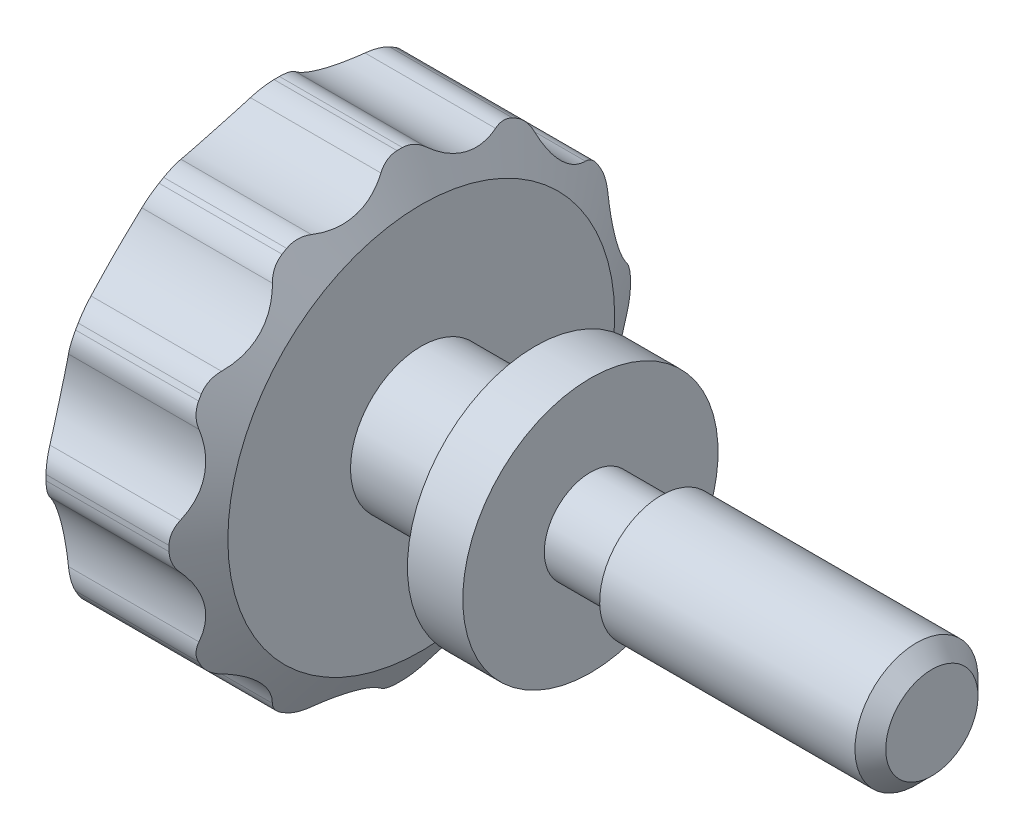
SolidWorks part; units mm, degrees
ref_plane "Спереди" through (0, 0, 0) normal (0, 0, 1) x (1, 0, 0)
ref_plane "Сверху" through (0, 0, 0) normal (0, 1, 0) x (1, 0, 0)
ref_plane "Справа" through (0, 0, 0) normal (1, 0, 0) x (0, 0, -1)
sketch "Эскиз1" plane through (0, 0, 0) normal (0, 0, 1) x (1, 0, 0)
  line L0 (0, 0) -> (-20.2, 0) construction
  line L2 (-21.3, 7.5) -> (-17.3, 7.5)
  line L4 (-16.6, 2.3) -> (-12.9, 2.3)
  line L5 (-12.9, 2.3) -> (-12.9, 4.15)
  line L6 (-12.9, 4.15) -> (-11.1, 4.15)
  line L8 (-8.8, 2) -> (0, 2)
  line L9 (0, 2) -> (0, 0)
  line L10 (-11.1, 4.15) -> (-11.1, 1.5)
  line L11 (-11.1, 1.5) -> (-8.8, 1.5)
  line L12 (-8.8, 1.5) -> (-8.8, 2)
  line L13 (-17.3, 7.5) -> (-16.6, 6.2876)
  line L14 (-16.6, 6.2876) -> (-16.6, 2.3)
  line L15 (-21.3, 7.5) -> (-22, 6.2876)
  line L16 (-22, 6.2876) -> (-22, 5.5)
  line L17 (-22, 5.5) -> (-21, 1.9144)
  line L18 (-21, 1.9144) -> (-20.2, 1.7)
  line L19 (-20.2, 1.7) -> (-20.2, 0)
  line L20 (0, 0) -> (-20.2, 0)
  dimension "D1" = 4
  dimension "D2" = 8.3
  dimension "D3" = 2.3
  dimension "D4" = 3
  dimension "D5" = 1.8
  dimension "D6" = 3.7
  dimension "D7" = 30
  dimension "D8" = 30
  dimension "D9" = 0.7
  dimension "D10" = 15
  dimension "D11" = 3.4
  dimension "D12" = 15
  dimension "D13" = 1
  dimension "D14" = 1.8
  dimension "D15" = 11
  dimension "D16" = 22
  dimension "D17" = 5.4
  dimension "D18" = 4.6
revolve "Повернуть1" add sketch "Эскиз1" angle 360 about L0
cosmetic thread "Условное изображение резьбы3" [suppressed] parameters "D2"=3.242
chamfer "Фаска1" distance 0.5 angle 45 1 edges at (0, 2, 0)
sketch "Эскиз2" plane through (-22, 0, 0) normal (-1, 0, 0) x (0, 0, 1)
  line L0 (-0.52, 5.3013) -> (-0.52, 3.2717)
  line L1 (-4.3311, 3.101) -> (-2.5734, 2.0862)
  line L2 (4.3311, 3.101) -> (2.5734, 2.0862)
  line L3 (0.52, 5.3013) -> (0.52, 3.2717)
  line L4 (4.8511, -2.2003) -> (3.0934, -1.1855)
  line L5 (4.8511, 2.2003) -> (3.0934, 1.1855)
  line L6 (0.52, -5.3013) -> (0.52, -3.2717)
  line L7 (4.3311, -3.101) -> (2.5734, -2.0862)
  line L8 (-4.3311, -3.101) -> (-2.5734, -2.0862)
  line L9 (-0.52, -5.3013) -> (-0.52, -3.2717)
  line L10 (-4.8511, 2.2003) -> (-3.0934, 1.1855)
  line L11 (-4.8511, -2.2003) -> (-3.0934, -1.1855)
  line L12 (0, 0) -> (0, 5.55) construction
  arc A0 (-0.677, 3.0764) -> (-2.3257, 2.1245) centre (0, 0) ccw
  arc A1 (-0.7469, 5.4995) -> (-4.3893, 3.3966) centre (0, 0) ccw
  arc A2 (-2.3257, 2.1245) -> (-2.5734, 2.0862) centre (-2.4734, 2.2594) cw
  arc A3 (-0.52, 3.2717) -> (-0.677, 3.0764) centre (-0.72, 3.2717) cw
  arc A4 (-0.52, 5.3013) -> (-0.7469, 5.4995) centre (-0.72, 5.3013) ccw
  arc A5 (-4.3893, 3.3966) -> (-4.3311, 3.101) centre (-4.2311, 3.2742) ccw
  arc A6 (2.3257, 2.1245) -> (0.677, 3.0764) centre (0, 0) ccw
  arc A7 (4.3893, 3.3966) -> (0.7469, 5.4995) centre (0, 0) ccw
  arc A8 (0.677, 3.0764) -> (0.52, 3.2717) centre (0.72, 3.2717) cw
  arc A9 (2.5734, 2.0862) -> (2.3257, 2.1245) centre (2.4734, 2.2594) cw
  arc A10 (4.3311, 3.101) -> (4.3893, 3.3966) centre (4.2311, 3.2742) ccw
  arc A11 (0.7469, 5.4995) -> (0.52, 5.3013) centre (0.72, 5.3013) ccw
  arc A12 (3.0027, -0.9519) -> (3.0027, 0.9519) centre (0, 0) ccw
  arc A13 (5.1362, -2.1029) -> (5.1362, 2.1029) centre (0, 0) ccw
  arc A14 (3.0027, 0.9519) -> (3.0934, 1.1855) centre (3.1934, 1.0123) cw
  arc A15 (3.0934, -1.1855) -> (3.0027, -0.9519) centre (3.1934, -1.0123) cw
  arc A16 (4.8511, -2.2003) -> (5.1362, -2.1029) centre (4.9511, -2.0271) ccw
  arc A17 (5.1362, 2.1029) -> (4.8511, 2.2003) centre (4.9511, 2.0271) ccw
  arc A18 (0.677, -3.0764) -> (2.3257, -2.1245) centre (0, 0) ccw
  arc A19 (0.7469, -5.4995) -> (4.3893, -3.3966) centre (0, 0) ccw
  arc A20 (2.3257, -2.1245) -> (2.5734, -2.0862) centre (2.4734, -2.2594) cw
  arc A21 (0.52, -3.2717) -> (0.677, -3.0764) centre (0.72, -3.2717) cw
  arc A22 (0.52, -5.3013) -> (0.7469, -5.4995) centre (0.72, -5.3013) ccw
  arc A23 (4.3893, -3.3966) -> (4.3311, -3.101) centre (4.2311, -3.2742) ccw
  arc A24 (-2.3257, -2.1245) -> (-0.677, -3.0764) centre (0, 0) ccw
  arc A25 (-4.3893, -3.3966) -> (-0.7469, -5.4995) centre (0, 0) ccw
  arc A26 (-0.677, -3.0764) -> (-0.52, -3.2717) centre (-0.72, -3.2717) cw
  arc A27 (-2.5734, -2.0862) -> (-2.3257, -2.1245) centre (-2.4734, -2.2594) cw
  arc A28 (-4.3311, -3.101) -> (-4.3893, -3.3966) centre (-4.2311, -3.2742) ccw
  arc A29 (-0.7469, -5.4995) -> (-0.52, -5.3013) centre (-0.72, -5.3013) ccw
  arc A30 (-3.0027, 0.9519) -> (-3.0027, -0.9519) centre (0, 0) ccw
  arc A31 (-5.1362, 2.1029) -> (-5.1362, -2.1029) centre (0, 0) ccw
  arc A32 (-3.0027, -0.9519) -> (-3.0934, -1.1855) centre (-3.1934, -1.0123) cw
  arc A33 (-3.0934, 1.1855) -> (-3.0027, 0.9519) centre (-3.1934, 1.0123) cw
  arc A34 (-4.8511, 2.2003) -> (-5.1362, 2.1029) centre (-4.9511, 2.0271) ccw
  arc A35 (-5.1362, -2.1029) -> (-4.8511, -2.2003) centre (-4.9511, -2.0271) ccw
  point P77 (0, 0)
  dimension "D1" = 0.2
  dimension "D2" = 3.15
  dimension "D3" = 5.55
  dimension "D5" = 1.04
  dimension "D4" = 6
extrude "Вырез-Вытянуть1" cut sketch "Эскиз2" against normal blind 3.4
sketch "Эскиз3" plane through (-22, 0, 0) normal (-1, 0, 0) x (0, 0, 1)
  arc A0 (-0.5, 7.4833) -> (-3.3086, 6.7307) centre (-2.4804, 9.2571) cw
  circle A1 centre (0, 0) radius 7.5 construction
  arc A3 (3.3086, 6.7307) -> (0.5, 7.4833) centre (2.4804, 9.2571) cw
  arc A4 (6.2307, 4.1747) -> (4.1747, 6.2307) centre (6.7767, 6.7767) cw
  arc A5 (7.4833, 0.5) -> (6.7307, 3.3086) centre (9.2571, 2.4804) cw
  arc A6 (6.7307, -3.3086) -> (7.4833, -0.5) centre (9.2571, -2.4804) cw
  arc A7 (4.1747, -6.2307) -> (6.2307, -4.1747) centre (6.7767, -6.7767) cw
  arc A8 (0.5, -7.4833) -> (3.3086, -6.7307) centre (2.4804, -9.2571) cw
  arc A9 (-3.3086, -6.7307) -> (-0.5, -7.4833) centre (-2.4804, -9.2571) cw
  arc A10 (-6.2307, -4.1747) -> (-4.1747, -6.2307) centre (-6.7767, -6.7767) cw
  arc A11 (-7.4833, -0.5) -> (-6.7307, -3.3086) centre (-9.2571, -2.4804) cw
  arc A12 (-6.7307, 3.3086) -> (-7.4833, 0.5) centre (-9.2571, 2.4804) cw
  arc A13 (-4.1747, 6.2307) -> (-6.2307, 4.1747) centre (-6.7767, 6.7767) cw
  arc A14 (-0.5, 7.4833) -> (0.5, 7.4833) centre (0, 0) cw construction
  arc A15 (-3.3086, 6.7307) -> (-0.5, 7.4833) centre (0, 0) cw
  arc A16 (0.5, 7.4833) -> (3.3086, 6.7307) centre (0, 0) cw
  arc A17 (4.1747, 6.2307) -> (6.2307, 4.1747) centre (0, 0) cw
  arc A18 (6.7307, 3.3086) -> (7.4833, 0.5) centre (0, 0) cw
  arc A19 (7.4833, -0.5) -> (6.7307, -3.3086) centre (0, 0) cw
  arc A20 (6.2307, -4.1747) -> (4.1747, -6.2307) centre (0, 0) cw
  arc A21 (3.3086, -6.7307) -> (0.5, -7.4833) centre (0, 0) cw
  arc A22 (-0.5, -7.4833) -> (-3.3086, -6.7307) centre (0, 0) cw
  arc A23 (-4.1747, -6.2307) -> (-6.2307, -4.1747) centre (0, 0) cw
  arc A24 (-6.7307, -3.3086) -> (-7.4833, -0.5) centre (0, 0) cw
  arc A25 (-7.4833, 0.5) -> (-6.7307, 3.3086) centre (0, 0) cw
  arc A26 (-6.2307, 4.1747) -> (-4.1747, 6.2307) centre (0, 0) cw
  circle A27 centre (0, 0) radius 6.925 construction
  point P12 (0, 7.5)
  point P43 (0, 0)
  point P70 (0, 0)
  dimension "D4" = 13.85
  dimension "D2" = 1
  dimension "D1" = 12
  dimension "D3" = 12
extrude "Вырез-Вытянуть2" cut sketch "Эскиз3" against normal up to surface (5.4 mm away)
fillet "Скругление1" radius 1 24 edges at (-19.3, 7.4833, 0.5) (-19.3, 6.7307, 3.3086) (-19.3, 6.2307, 4.1747) (-19.3, 4.1747, 6.2307) (-19.3, 3.3086, 6.7307) (-19.3, 0.5, 7.4833) (-19.3, -0.5, 7.4833) (-19.3, -3.3086, 6.7307) (-19.3, -4.1747, 6.2307) (-19.3, -6.2307, 4.1747) (-19.3, -6.7307, 3.3086) (-19.3, -7.4833, 0.5) (-19.3, -7.4833, -0.5) (-19.3, -6.7307, -3.3086) (-19.3, -6.2307, -4.1747) (-19.3, -4.1747, -6.2307) (-19.3, -3.3086, -6.7307) (-19.3, -0.5, -7.4833) (-19.3, 0.5, -7.4833) (-19.3, 3.3086, -6.7307) (-19.3, 4.1747, -6.2307) (-19.3, 6.2307, -4.1747) (-19.3, 6.7307, -3.3086) (-19.3, 7.4833, -0.5)
thread "Резьба1" [suppressed] pitch 0.7 start angle 0, offset 0, length 10, pitch 0.7, diameter 4
ref_plane "Плоскость1" through (-8.8, 0, -2) normal (0, -1, 0) x (0, 0, -1)
sketch "Профиль резьбы1" plane through (-8.8, 0, -2) normal (0, -1, 0) x (0, 0, -1)
  line L0 (0, 0) -> (0, 0.7) construction
  line L1 (0, 0.525) -> (-0.3789, 0.3062)
  line L2 (-0.3789, 0.3062) -> (-0.3789, 0.2187)
  line L3 (-0.3789, 0.2187) -> (0, 0)
  line L4 (-0.3789, 0.2625) -> (0, 0.2625) construction
  line L11 (0, 0.525) -> (0, 0)
  point P6 (0, 0)
  dimension "Шаг" = 0.7
  dimension "Высота_профиля" = 0.3789
  dimension "Вершина_резьбы" = 0.0875
  dimension "Угол_профиля" = 60
